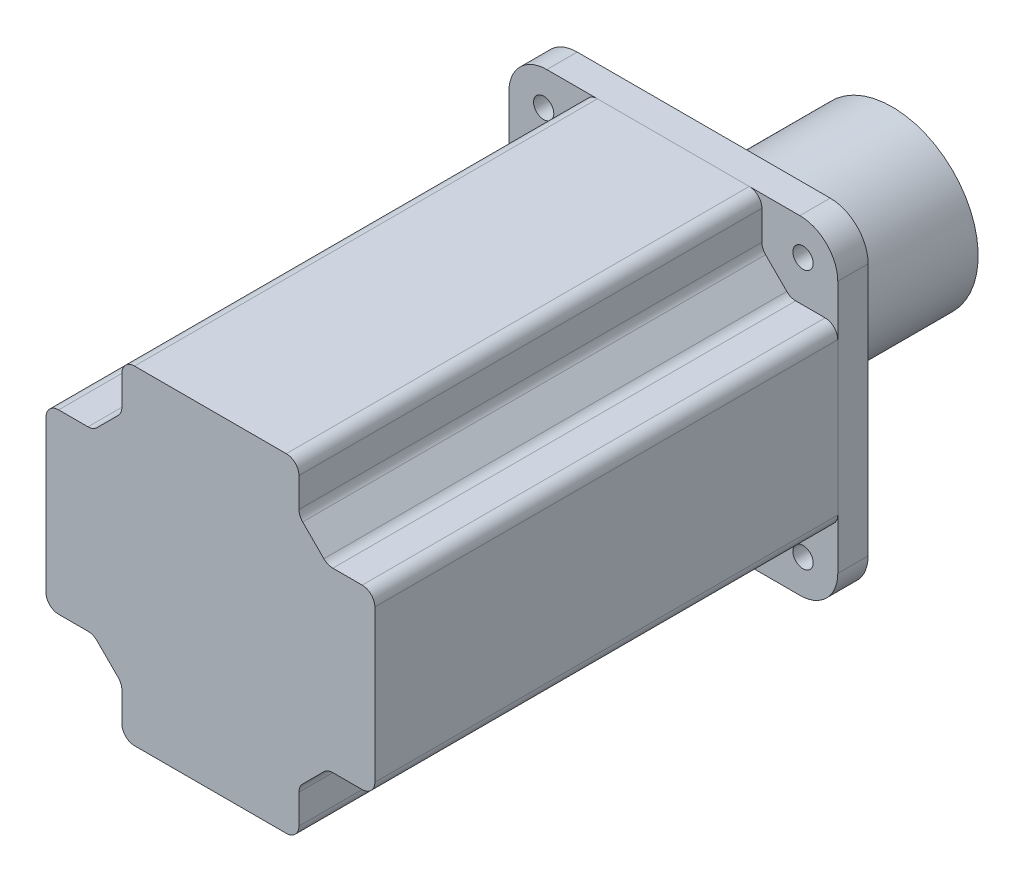
SolidWorks part; units mm, degrees
ref_plane "Front Plane" through (0, 0, 0) normal (0, 0, 1) x (1, 0, 0)
ref_plane "Top Plane" through (0, 0, 0) normal (0, 1, 0) x (1, 0, 0)
ref_plane "Right Plane" through (0, 0, 0) normal (1, 0, 0) x (0, 0, -1)
sketch "Sketch1" plane through (0, 0, 0) normal (0, 0, 1) x (1, 0, 0)
  line L0 (0, 65) -> (0, -65) construction
  line L1 (-50, 65) -> (50, 65)
  line L2 (-65, 50) -> (-65, -50)
  line L3 (-50, -65) -> (50, -65)
  line L4 (65, 50) -> (65, -50)
  line L5 (-65, 65) -> (65, -65) construction
  line L6 (-65, -65) -> (65, 65) construction
  line L7 (-65, 0) -> (65, 0) construction
  circle A0 centre (0, 0) radius 72.5
  circle A1 centre (-51.2652, 51.2652) radius 4
  circle A2 centre (51.2652, 51.2652) radius 4
  circle A3 centre (-51.2652, -51.2652) radius 4
  circle A4 centre (51.2652, -51.2652) radius 4
  arc A5 (-65, -50) -> (-50, -65) centre (-50, -50) ccw
  arc A6 (50, -65) -> (65, -50) centre (50, -50) ccw
  arc A7 (50, 65) -> (65, 50) centre (50, 50) cw
  arc A8 (-50, 65) -> (-65, 50) centre (-50, 50) ccw
  point P0 (0, 0)
  dimension "D3" = 145
  dimension "D4" = 8
  dimension "D5" = 15
  dimension "D1" = 130
  dimension "D2" = 130
extrude "Boss-Extrude1" add sketch "Sketch1" along normal blind 12 contours A4 A0 L4 A2 L1 A1 L2 A3 L3 | L1 A8 L2 A0 A1 | L2 A5 L3 A0 A3 | L3 A6 L4 A0 A4 | A7 L1 A0 A2 L4
sketch "Sketch2" plane through (0, 0, 12) normal (0, 0, 1) x (1, 0, 0)
  line L0 (-65, 35) -> (-46.3137, 35)
  line L1 (-46.3137, 35) -> (-35, 46.3137)
  line L2 (-35, 46.3137) -> (-35, 65)
  line L3 (0, 65) -> (0, -65) construction
  line L4 (65, -50) -> (65, 50)
  line L5 (50, 65) -> (-50, 65)
  line L6 (-65, 50) -> (-65, -50)
  line L7 (-50, -65) -> (50, -65)
  line L8 (65, -50) -> (65, 50)
  line L9 (50, 65) -> (-50, 65)
  line L10 (-65, 50) -> (-65, -50)
  line L11 (-50, -65) -> (50, -65)
  line L12 (-65, 0) -> (65, 0) construction
  line L13 (35, 46.3137) -> (35, 65)
  line L14 (46.3137, 35) -> (35, 46.3137)
  line L15 (65, 35) -> (46.3137, 35)
  line L16 (65, -35) -> (46.3137, -35)
  line L17 (46.3137, -35) -> (35, -46.3137)
  line L18 (35, -46.3137) -> (35, -65)
  line L19 (-35, -46.3137) -> (-35, -65)
  line L20 (-46.3137, -35) -> (-35, -46.3137)
  line L21 (-65, -35) -> (-46.3137, -35)
  arc A4 (50, -65) -> (65, -50) centre (50, -50) ccw
  arc A5 (65, 50) -> (50, 65) centre (50, 50) ccw
  arc A6 (-50, 65) -> (-65, 50) centre (-50, 50) ccw
  arc A7 (-65, -50) -> (-50, -65) centre (-50, -50) ccw
  arc A8 (50, -65) -> (65, -50) centre (50, -50) ccw
  arc A9 (65, 50) -> (50, 65) centre (50, 50) ccw
  arc A10 (-50, 65) -> (-65, 50) centre (-50, 50) ccw
  arc A11 (-65, -50) -> (-50, -65) centre (-50, -50) ccw
  line M22 (-65, 50) -> (-65, -50)
  dimension "D2" = 135
  dimension "D3" = 30
  dimension "D4" = 16
  dimension "D1" = 0
extrude "Boss-Extrude2" add sketch "Sketch2" along normal offset from surface (183 mm away) 195 separate body contours L21 L20 L19 L11 L18 L17 L16 L8 L15 L14 L13 L9 L2 L1 L0 M22 up to face at (0, 0, 0)
fillet "Fillet1" radius 5 16 edges at (-65, -35, 103.5) (-46.3137, -35, 103.5) (-35, -46.3137, 103.5) (-35, -65, 103.5) (35, -65, 103.5) (35, -46.3137, 103.5) (46.3137, -35, 103.5) (65, -35, 103.5) (65, 35, 103.5) (-65, 35, 103.5) (-46.3137, 35, 103.5) (-35, 46.3137, 103.5) (46.3137, 35, 103.5) (35, 46.3137, 103.5) (-35, 65, 103.5) (35, 65, 103.5)
sketch "Sketch4" plane through (0, 0, 0) normal (0, 0, -1) x (-1, 0, 0)
  circle A0 centre (0, 0) radius 55
  dimension "D1" = 110
extrude "Boss-Extrude4" add sketch "Sketch4" along normal blind 8
chamfer "Chamfer1" distance 6 angle 70 1 edges at (-55, 0, -8)
sketch "Sketch3" plane through (0, 0, -8) normal (0, 0, -1) x (-1, 0, 0)
  circle A0 centre (0, 0) radius 34
  dimension "D1" = 68
extrude "Boss-Extrude3" add sketch "Sketch3" along normal blind 66.5
